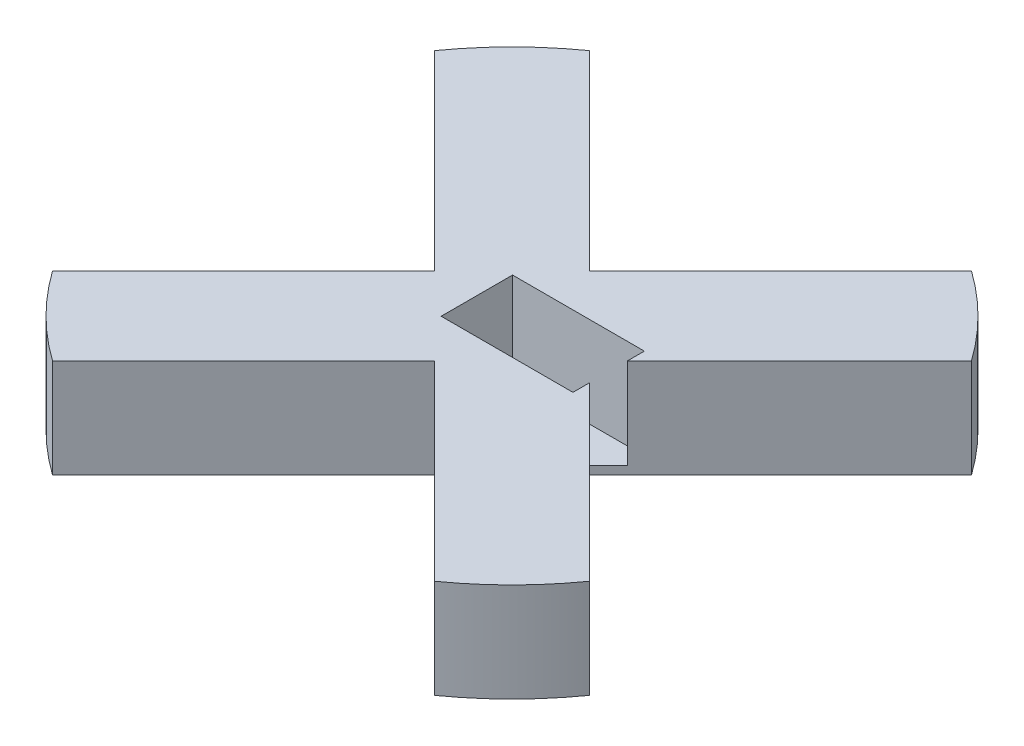
SolidWorks part; units mm, degrees
ref_plane "Front Plane" through (0, 0, 0) normal (0, 0, 1) x (1, 0, 0)
ref_plane "Top Plane" through (0, 0, 0) normal (0, 1, 0) x (1, 0, 0)
ref_plane "Right Plane" through (0, 0, 0) normal (1, 0, 0) x (0, 0, -1)
sketch "Sketch2" plane through (0, 0, 0) normal (0, 1, 0) x (1, 0, 0)
  line L0 (-42.4264, -42.4264) -> (42.4264, 42.4264) construction
  line L1 (14.1421, 0) -> (-14.1421, 0) construction
  line L2 (0, 0) -> (0, 14.1421) construction
  line L3 (14.1421, 0) -> (48.9041, 34.7619)
  line L4 (-42.4264, 42.4264) -> (42.4264, -42.4264) construction
  line L5 (0, -60) -> (0, 60) construction
  line L6 (0, 14.1421) -> (34.7619, 48.9041)
  line L7 (0, -14.1421) -> (34.7619, -48.9041)
  line L8 (0, -14.1421) -> (-34.7619, -48.9041)
  line L9 (0, 14.1421) -> (-34.7619, 48.9041)
  line L10 (-14.1421, 0) -> (-48.9041, -34.7619)
  line L11 (14.1421, 0) -> (48.9041, -34.7619)
  line L12 (-14.1421, 0) -> (-48.9041, 34.7619)
  circle A0 centre (0, 0) radius 60 construction
  arc A1 (-48.9041, 34.7619) -> (-34.7619, 48.9041) centre (0, 0) ccw construction
  arc A2 (-34.7619, 48.9041) -> (-48.9041, 34.7619) centre (0, 0) ccw
  arc A3 (34.7619, 48.9041) -> (48.9041, 34.7619) centre (0, 0) cw
  arc A4 (34.7619, -48.9041) -> (48.9041, -34.7619) centre (0, 0) ccw
  arc A5 (-34.7619, -48.9041) -> (-48.9041, -34.7619) centre (0, 0) cw
  point P9 (0, 0)
  point P12 (0, 0)
  point P15 (0, 0)
  dimension "D1" = 120
  dimension "D2" = 45
  dimension "D3" = 20
  dimension "D4" = 45
  dimension "D5" = 10
extrude "Boss-Extrude2" add sketch "Sketch2" along normal blind 18
sketch "Sketch6" plane through (0, 18, 0) normal (0, 1, 0) x (1, 0, 0)
sketch "Sketch7" plane through (0, 18, 0) normal (0, 1, 0) x (1, 0, 0)
  line L0 (0, 0) -> (5.6, 0) construction
  line L1 (17.6, -6.5) -> (-6.4, -6.5)
  line L2 (17.6, -6.5) -> (17.6, 6.5)
  line L3 (17.6, 6.5) -> (-6.4, 6.5)
  line L4 (-6.4, -6.5) -> (-6.4, 6.5)
  line L5 (17.6, -6.5) -> (-6.4, 6.5) construction
  line L6 (17.6, 6.5) -> (-6.4, -6.5) construction
  point P0 (0, 0)
  dimension "D1" = 5.6
  dimension "D2" = 12
  dimension "D3" = 13
extrude "Cut-Extrude8" cut sketch "Sketch7" against normal blind 16.5
